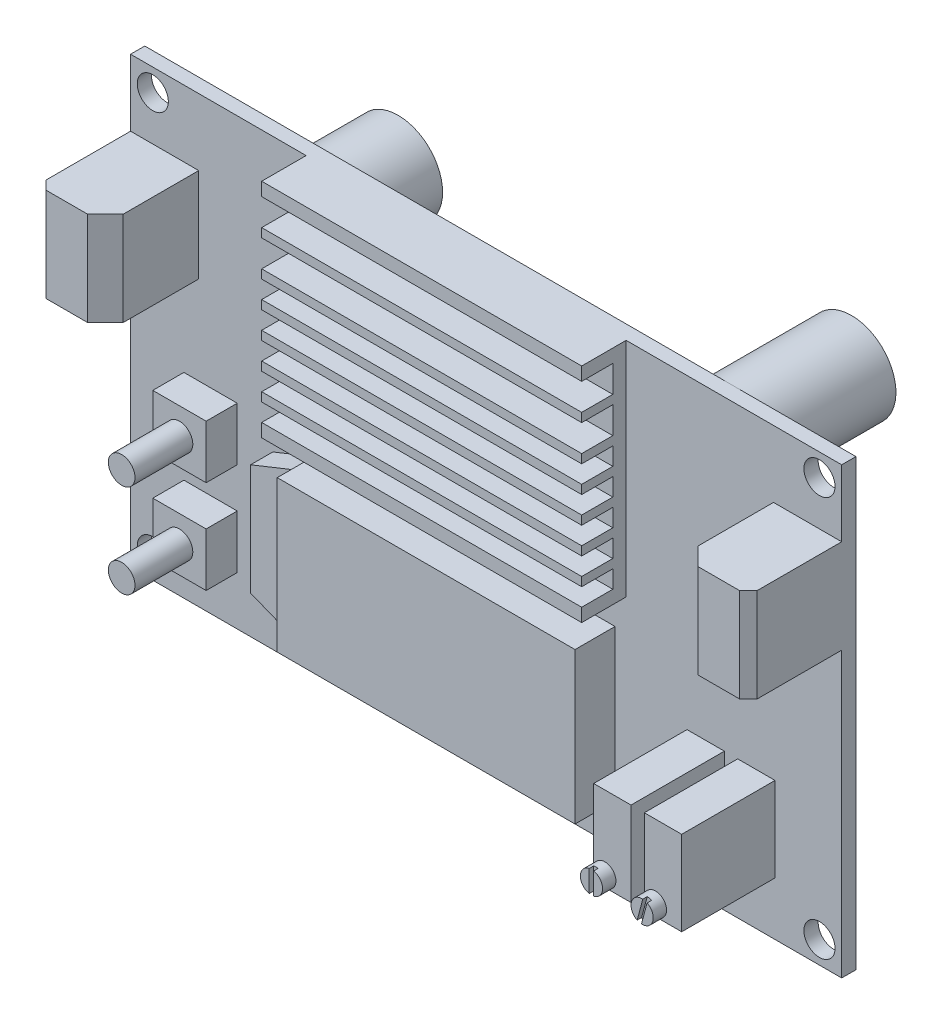
SolidWorks part; units mm, degrees
ref_plane "Front" through (0, 0, 0) normal (0, 0, 1) x (1, 0, 0)
ref_plane "Top" through (0, 0, 0) normal (0, 1, 0) x (1, 0, 0)
ref_plane "Right" through (0, 0, 0) normal (1, 0, 0) x (0, 0, -1)
sketch "Sketch1" plane through (0, 0, 0) normal (0, 0, 1) x (1, 0, 0)
  line L0 (-37.5, 22.5) -> (-37.5, -22.5) construction
  line L1 (40, -25) -> (-40, -25)
  line L2 (40, -25) -> (40, 25)
  line L3 (40, 25) -> (-40, 25)
  line L4 (-40, -25) -> (-40, 25)
  line L5 (40, -25) -> (-40, 25) construction
  line L6 (40, 25) -> (-40, -25) construction
  line L7 (-37.5, -22.5) -> (37.5, -22.5) construction
  line L8 (37.5, -22.5) -> (37.5, 22.5) construction
  line L9 (37.5, 22.5) -> (-37.5, 22.5) construction
  circle A0 centre (-37.5, 22.5) radius 1.75
  circle A1 centre (-37.5, -22.5) radius 1.75
  circle A2 centre (37.5, -22.5) radius 1.75
  circle A3 centre (37.5, 22.5) radius 1.75
  point P0 (0, 0)
  point P14 (0, 22.5)
  point P15 (-37.5, 0)
  dimension "D3" = 3.5
  dimension "D1" = 80
  dimension "D2" = 50
  dimension "D4" = 45
  dimension "D5" = 75
extrude "Boss-Extrude1" add sketch "Sketch1" along normal blind 1.6
sketch "Sketch2" plane through (0, 0, 1.6) normal (0, 0, 1) x (1, 0, 0)
  line L0 (40, -25) -> (40, 25) construction
  line L1 (22.6, -19) -> (26.8, -19)
  line L2 (22.6, -19) -> (22.6, -9.5)
  line L3 (22.6, -9.5) -> (26.8, -9.5)
  line L4 (26.8, -19) -> (26.8, -9.5)
  line L5 (22.6, -19) -> (26.8, -9.5) construction
  line L6 (22.6, -9.5) -> (26.8, -19) construction
  line L7 (28.3, -19) -> (32.5, -19)
  line L8 (28.3, -19) -> (28.3, -9.5)
  line L9 (28.3, -9.5) -> (32.5, -9.5)
  line L10 (32.5, -19) -> (32.5, -9.5)
  line L11 (28.3, -19) -> (32.5, -9.5) construction
  line L12 (28.3, -9.5) -> (32.5, -19) construction
  line L13 (32.33, 6.94) -> (40, 6.94)
  line L14 (32.33, 6.94) -> (32.33, 17.5)
  line L15 (32.33, 17.5) -> (40, 17.5)
  line L16 (40, 6.94) -> (40, 17.5)
  line L17 (32.33, 6.94) -> (40, 17.5) construction
  line L18 (32.33, 17.5) -> (40, 6.94) construction
  line L19 (-40, 25) -> (-40, -25) construction
  line L20 (-32.33, 6.94) -> (-40, 6.94)
  line L21 (-32.33, 6.94) -> (-32.33, 17.5)
  line L22 (-32.33, 17.5) -> (-40, 17.5)
  line L23 (-40, 6.94) -> (-40, 17.5)
  line L24 (-32.33, 6.94) -> (-40, 17.5) construction
  line L25 (-32.33, 17.5) -> (-40, 6.94) construction
  line L26 (40, 25) -> (-40, 25) construction
  line L27 (-40, -25) -> (40, -25) construction
  point P0 (24.7, -14.25)
  point P5 (30.4, -14.25)
  point P10 (36.165, 12.22)
  point P17 (-36.165, 12.22)
  dimension "D1" = 7.67
  dimension "D2" = 10.56
  dimension "D3" = 7.5
  dimension "D4" = 9.5
  dimension "D5" = 4.2
  dimension "D6" = 1.5
  dimension "D7" = 7.5
  dimension "D8" = 6
extrude "Boss-Extrude2" add sketch "Sketch2" along normal blind 10.5
chamfer "Chamfer1" distance 2 angle 45 2 edges at (-32.33, 12.22, 12.1) (32.33, 12.22, 12.1)
chamfer "Chamfer2" distance 1 angle 45 2 edges at (40, 12.22, 12.1) (-40, 12.22, 12.1)
sketch "Sketch3" plane through (0, 0, 12.1) normal (0, 0, 1) x (1, 0, 0)
  line L0 (22.6, -19) -> (26.8, -19) construction
  line L1 (22.6, -9.5) -> (22.6, -19) construction
  line L2 (28.3, -9.5) -> (28.3, -19) construction
  line L3 (28.3, -19) -> (32.5, -19) construction
  circle A0 centre (23.85, -17.75) radius 1.25
  circle A1 centre (29.55, -17.75) radius 1.25
  dimension "D1" = 2.5
extrude "Boss-Extrude3" add sketch "Sketch3" along normal blind 1.5
sketch "Sketch4" plane through (0, 0, 13.6) normal (0, 0, 1) x (1, 0, 0)
  line L0 (23.6, -16.5253) -> (23.6, -18.9747)
  line L1 (24.1, -16.5253) -> (24.1, -18.9747)
  line L2 (28.9915, -18.8683) -> (29.6255, -16.5023)
  line L3 (29.4745, -18.9977) -> (30.1085, -16.6317)
  line L4 (28.3, -9.5) -> (28.3, -19) construction
  arc A0 (24.1, -16.5253) -> (23.6, -16.5253) centre (23.85, -17.75) ccw
  circle A1 centre (23.85, -17.75) radius 1.25
  arc A2 (23.6, -18.9747) -> (24.1, -18.9747) centre (23.85, -17.75) ccw
  circle A3 centre (29.55, -17.75) radius 1.25
  arc A4 (28.9915, -18.8683) -> (29.4745, -18.9977) centre (29.55, -17.75) ccw
  arc A5 (30.1085, -16.6317) -> (29.6255, -16.5023) centre (29.55, -17.75) ccw
  dimension "D3" = 0.5
  dimension "D4" = 0.5
  dimension "D5" = 15
  dimension "D1" = 0
  dimension "D2" = 0
extrude "Cut-Extrude1" cut sketch "Sketch4" against normal blind 0.5
sketch "Sketch5" plane through (0, 0, 1.6) normal (0, 0, 1) x (1, 0, 0)
  line L0 (-40, -25) -> (40, -25) construction
  line L1 (-19, -20.5) -> (14.5, -20.5)
  line L2 (-19, -20.5) -> (-19, -3.5)
  line L3 (-19, -3.5) -> (14.5, -3.5)
  line L4 (14.5, -20.5) -> (14.5, -3.5)
  line L5 (-19, -20.5) -> (14.5, -3.5) construction
  line L6 (-19, -3.5) -> (14.5, -20.5) construction
  line L7 (-40, 6.94) -> (-40, -25) construction
  point P0 (-2.25, -12)
  dimension "D1" = 33.5
  dimension "D2" = 17
  dimension "D3" = 4.5
  dimension "D4" = 21
extrude "Boss-Extrude4" add sketch "Sketch5" along normal blind 4.5
sketch "Sketch6" plane through (0, 0, 1.6) normal (0, 0, 1) x (1, 0, 0)
  line L0 (-19, -20.25) -> (-24, -18.25)
  line L1 (-19, -3.5) -> (-19, -20.5) construction
  line L2 (-24, -18.25) -> (-24, -5.75)
  line L3 (-24, -5.75) -> (-19, -3.75)
  line L4 (-19, -3.75) -> (-19, -20.25) construction
  line L5 (-24, -12) -> (-19, -12) construction
  line M33 (-19, -20.5) -> (-19, -3.5)
  dimension "D1" = 12.5
  dimension "D2" = 16.5
  dimension "D3" = 5
extrude "Boss-Extrude5" add sketch "Sketch6" along normal blind 2.5 contours L3 L2 L0 M33
sketch "Sketch7" plane through (0, 0, 1.6) normal (0, 0, 1) x (1, 0, 0)
  line L0 (-40, -25) -> (40, -25) construction
  line L1 (-34, -13.5) -> (-28, -13.5)
  line L2 (-34, -13.5) -> (-34, -19.5)
  line L3 (-34, -19.5) -> (-28, -19.5)
  line L4 (-28, -13.5) -> (-28, -19.5)
  line L5 (-34, -13.5) -> (-28, -19.5) construction
  line L6 (-34, -19.5) -> (-28, -13.5) construction
  line L7 (-34, -3) -> (-28, -3)
  line L8 (-34, -3) -> (-34, -9)
  line L9 (-34, -9) -> (-28, -9)
  line L10 (-28, -3) -> (-28, -9)
  line L11 (-34, -3) -> (-28, -9) construction
  line L12 (-34, -9) -> (-28, -3) construction
  line L13 (-40, 6.94) -> (-40, -25) construction
  point P0 (-31, -16.5)
  point P5 (-31, -6)
  dimension "D1" = 6
  dimension "D2" = 4.5
  dimension "D3" = 5.5
  dimension "D4" = 6
extrude "Boss-Extrude6" add sketch "Sketch7" along normal blind 3.5
sketch "Sketch8" plane through (0, 0, 5.1) normal (0, 0, 1) x (1, 0, 0)
  line L0 (-28, -13.5) -> (-34, -13.5) construction
  line L1 (-34, -13.5) -> (-34, -19.5) construction
  line L2 (-34, -3) -> (-34, -9) construction
  line L3 (-28, -3) -> (-34, -3) construction
  circle A0 centre (-31, -6) radius 1.5
  circle A1 centre (-31, -16.5) radius 1.5
  point P6 (-31, -13.5)
  point P9 (-34, -16.5)
  point P12 (-34, -6)
  point P15 (-31, -3)
  dimension "D1" = 3
extrude "Boss-Extrude7" add sketch "Sketch8" along normal blind 6.5
sketch "Sketch9" plane through (0, 0, 1.6) normal (0, 0, 1) x (1, 0, 0)
  line L0 (40, 25) -> (-40, 25) construction
  line L1 (-20.25, 25) -> (15.75, 25)
  line L2 (-20.25, 25) -> (-20.25, 0)
  line L3 (-20.25, 0) -> (15.75, 0)
  line L4 (15.75, 25) -> (15.75, 0)
  line L5 (-20.25, 25) -> (15.75, 0) construction
  line L6 (-20.25, 0) -> (15.75, 25) construction
  line L7 (-2.25, -3.5) -> (-2.25, 12.5) construction
  line L8 (14.5, -3.5) -> (-19, -3.5) construction
  point P0 (-2.25, 12.5)
  dimension "D1" = 36
  dimension "D2" = 25
extrude "Boss-Extrude8" add sketch "Sketch9" along normal blind 1.5
sketch "Sketch10" plane through (0, 0, 3.1) normal (0, 0, 1) x (1, 0, 0)
  line L0 (15.75, 0) -> (15.75, 25) construction
  line L1 (-20.25, 0) -> (15.75, 0)
  line L2 (-20.25, 0) -> (-20.25, 1.5)
  line L3 (-20.25, 1.5) -> (15.75, 1.5)
  line L4 (15.75, 0) -> (15.75, 1.5)
  line L5 (15.75, 0) -> (15.75, 25) construction
  line L6 (-20.25, 25) -> (15.75, 25)
  line L7 (-20.25, 25) -> (-20.25, 23.5)
  line L8 (-20.25, 23.5) -> (15.75, 23.5)
  line L9 (15.75, 25) -> (15.75, 23.5)
  line L10 (-20.25, 25) -> (-20.25, 0) construction
  line L11 (-20.25, 4.4931) -> (15.75, 4.4931)
  line L12 (-20.25, 4.4931) -> (-20.25, 3.4931)
  line L13 (-20.25, 3.4931) -> (15.75, 3.4931)
  line L14 (15.75, 4.4931) -> (15.75, 3.4931)
  line L15 (-20.25, 25) -> (-20.25, 0) construction
  line L16 (-20.25, 6.4862) -> (15.75, 6.4862)
  line L17 (-20.25, 6.4862) -> (-20.25, 7.4862)
  line L18 (-20.25, 7.4862) -> (15.75, 7.4862)
  line L19 (15.75, 6.4862) -> (15.75, 7.4862)
  line L20 (-2.25, 23.5) -> (-2.25, 20.4828) construction
  line L21 (-20.25, 9.4793) -> (15.75, 9.4793)
  line L22 (-20.25, 9.4793) -> (-20.25, 10.4793)
  line L23 (-20.25, 10.4793) -> (15.75, 10.4793)
  line L24 (15.75, 9.4793) -> (15.75, 10.4793)
  line L25 (-20.25, 13.4724) -> (15.75, 13.4724)
  line L26 (-20.25, 13.4724) -> (-20.25, 12.4724)
  line L27 (-20.25, 12.4724) -> (15.75, 12.4724)
  line L28 (15.75, 13.4724) -> (15.75, 12.4724)
  line L29 (-20.25, 15.4655) -> (15.75, 15.4655)
  line L30 (-20.25, 15.4655) -> (-20.25, 16.4655)
  line L31 (-20.25, 16.4655) -> (15.75, 16.4655)
  line L32 (15.75, 15.4655) -> (15.75, 16.4655)
  line L33 (-20.25, 19.4828) -> (15.75, 19.4828)
  line L34 (-20.25, 19.4828) -> (-20.25, 20.4828)
  line L35 (-20.25, 20.4828) -> (15.75, 20.4828)
  line L36 (15.75, 19.4828) -> (15.75, 20.4828)
  line L37 (-2.25, 19.4828) -> (-2.25, 16.4655) construction
  line L38 (-2.25, 15.4655) -> (-2.25, 13.4724) construction
  line L39 (-2.25, 12.4724) -> (-2.25, 10.4793) construction
  line L40 (-2.25, 9.4793) -> (-2.25, 7.4862) construction
  line L41 (-2.25, 4.4931) -> (-2.25, 6.4862) construction
  line L42 (-2.25, 3.4931) -> (-2.25, 1.5) construction
  dimension "D1" = 1.5
  dimension "D2" = 1
extrude "Boss-Extrude9" add sketch "Sketch10" along normal blind 3.5
sketch "Sketch11" plane through (0, 0, 0) normal (0, 0, -1) x (-1, 0, 0)
  line L0 (-40, 25) -> (40, 25) construction
  line L1 (-40, -25) -> (-40, 25) construction
  line L2 (40, 25) -> (40, -25) construction
  circle A0 centre (-26, 20) radius 5
  circle A1 centre (25, 14) radius 5
  dimension "D1" = 10
  dimension "D2" = 14
  dimension "D3" = 15
  dimension "D4" = 11
extrude "Boss-Extrude10" add sketch "Sketch11" along normal blind 13.5
sketch "Sketch12" plane through (0, 0, 0) normal (0, 0, -1) x (-1, 0, 0)
  line L0 (-26, 25) -> (40, 25) construction
  line L1 (-40, -25) -> (-40, 25) construction
  circle A0 centre (-20.5, 4) radius 6.25
  circle A1 centre (-20.5, 4) radius 10.25
  dimension "D1" = 20.5
  dimension "D2" = 12.5
  dimension "D4" = 19.5
  dimension "D3" = 21
extrude "Boss-Extrude11" add sketch "Sketch12" along normal blind 8.25
